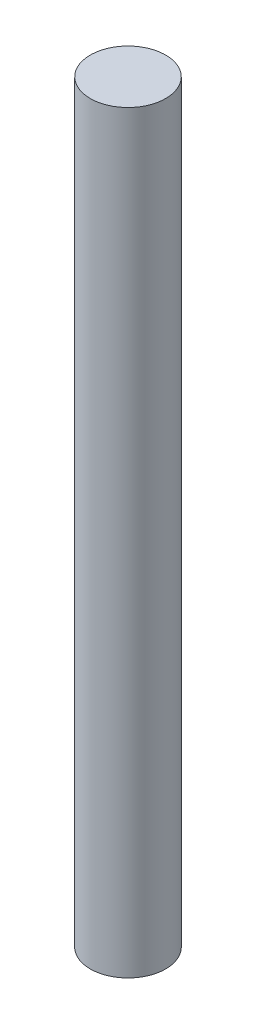
SolidWorks part; units mm, degrees
ref_plane "Alzado" through (0, 0, 0) normal (0, 0, 1) x (1, 0, 0)
ref_plane "Planta" through (0, 0, 0) normal (0, 1, 0) x (1, 0, 0)
ref_plane "Vista lateral" through (0, 0, 0) normal (1, 0, 0) x (0, 0, -1)
sketch "Croquis1" plane through (0, 0, 0) normal (0, 1, 0) x (1, 0, 0)
  circle A0 centre (0, 0) radius 5
  dimension "D1" = 10
extrude "Saliente-Extruir1" add sketch "Croquis1" along normal blind 100
